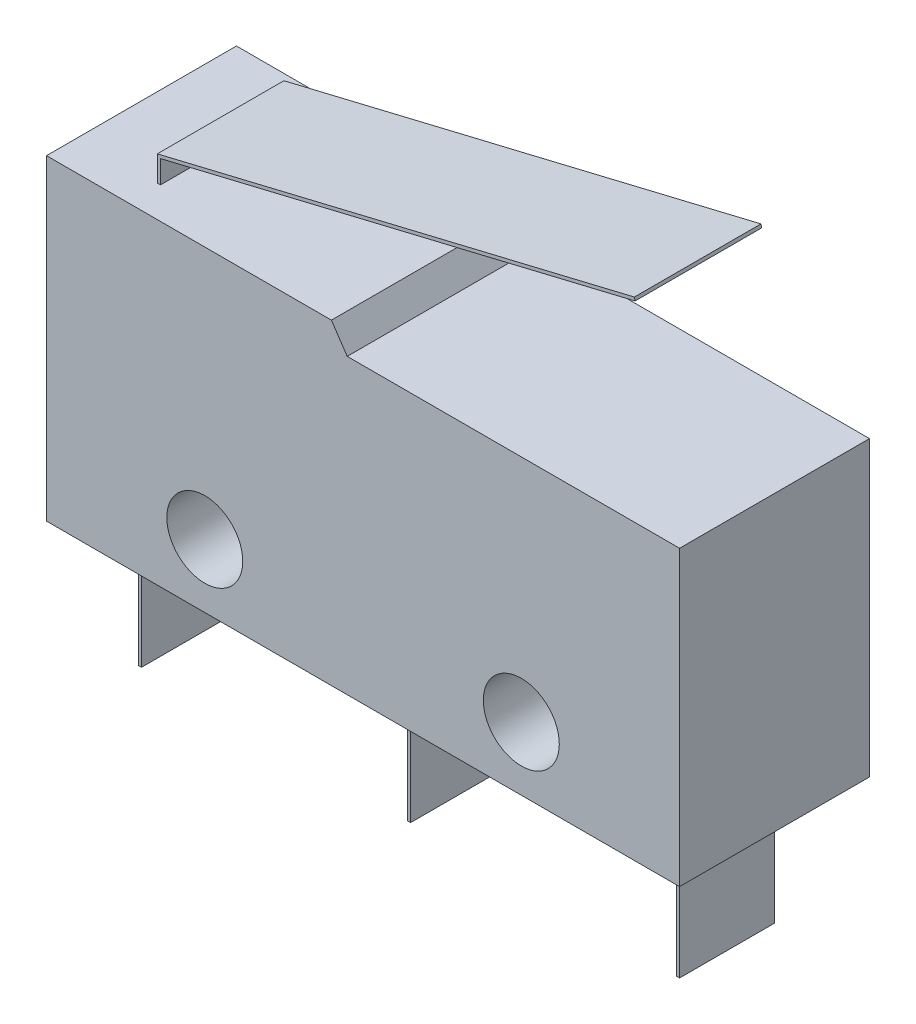
SolidWorks part; units mm, degrees
ref_plane "Front" through (0, 0, 0) normal (0, 0, 1) x (1, 0, 0)
ref_plane "Top" through (0, 0, 0) normal (0, 1, 0) x (1, 0, 0)
ref_plane "Right" through (0, 0, 0) normal (1, 0, 0) x (0, 0, -1)
sketch "Sketch1" plane through (0, 0, 0) normal (0, 0, 1) x (1, 0, 0)
  line L0 (-1, 5) -> (-0.5, 4.2583)
  line L1 (-10, 5) -> (10, 5)
  line L2 (-10, 5) -> (-10, -5)
  line L3 (-10, -5) -> (10, -5)
  line L4 (10, 5) -> (10, -5)
  line L5 (-10, 5) -> (10, -5) construction
  line L6 (-10, -5) -> (10, 5) construction
  line L7 (-0.5, 4.2583) -> (10, 4.2583)
  circle A0 centre (-5, -3) radius 1.2
  circle A1 centre (5, -3) radius 1.2
  point P0 (0, 0)
  dimension "D3" = 2.4
  dimension "D1" = 20
  dimension "D2" = 10
  dimension "D4" = 2
  dimension "D5" = 5
  dimension "D6" = 5
  dimension "D7" = 9
  dimension "D8" = 10.5
extrude "Boss-Extrude1" add sketch "Sketch1" along normal blind 6 contours L7 L0 L1 L2 L3 L4 A1 A0
sketch "Sketch2" plane through (0, 0, 6) normal (0, 0, 1) x (1, 0, 0)
  line L0 (-7.5, 5) -> (-7.5, 5.8)
  line L2 (-7.5, 5.8) -> (7.5717, 9.4184)
  line L4 (-10, 5) -> (-1, 5) construction
  line L5 (-10, 5) -> (-10, -5) construction
  dimension "D1" = 0.8
  dimension "D2" = 13.5
  dimension "D3" = 15.5
  dimension "D4" = 2.5
extrude "Extrude-Thin1" add sketch "Sketch2" against normal blind 4 from offset 1 thin contours L0 L2 offset against normal yes
sketch "Sketch3" plane through (0, -5, 0) normal (0, -1, 0) x (1, 0, 0)
  line L0 (-8.5, 4.5) -> (-8.5, 1.5)
  line L1 (-10, 6) -> (-10, 0) construction
  line L2 (-10, 6) -> (10, 6) construction
  line L3 (0, -3.3) -> (0, 3.3) construction
  line L4 (8.5, 4.5) -> (8.5, 1.5)
  line L5 (0, 4.5) -> (0, 1.5)
  dimension "D1" = 3
  dimension "D2" = 1.5
  dimension "D3" = 1.5
extrude "Extrude-Thin2" add sketch "Sketch3" along normal blind 4 thin
